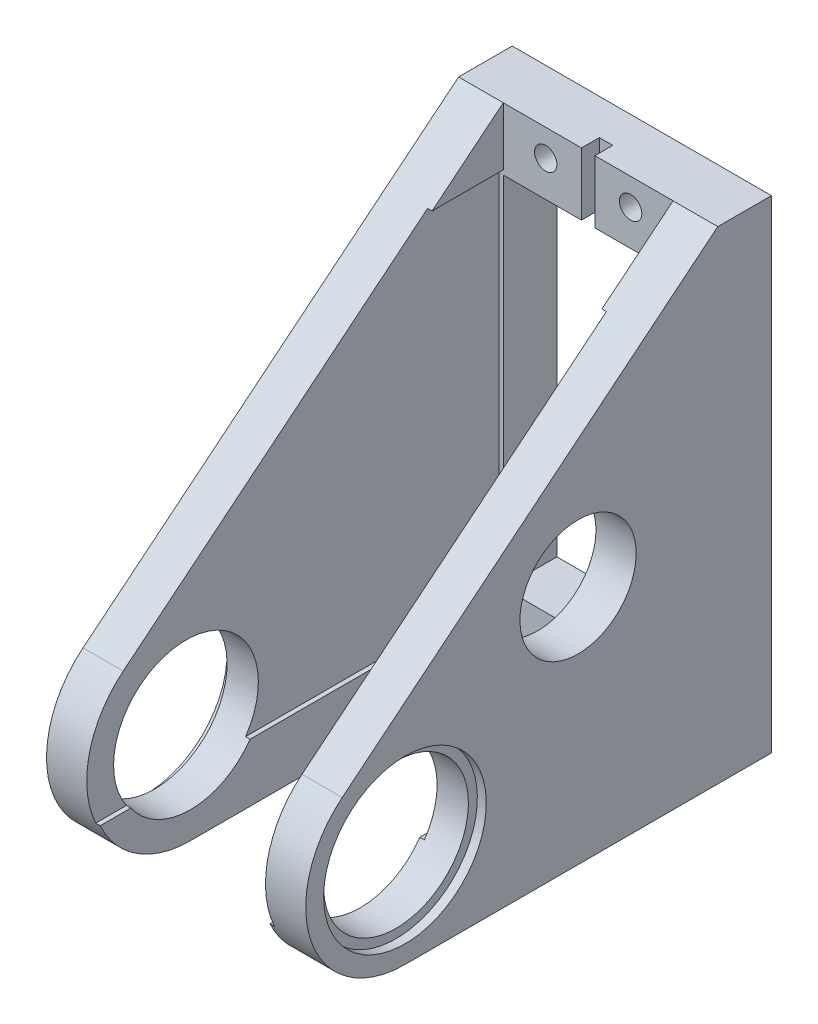
SolidWorks part; units mm, degrees
ref_plane "Спереди" through (0, 0, 0) normal (0, 0, 1) x (1, 0, 0)
ref_plane "Сверху" through (0, 0, 0) normal (0, 1, 0) x (1, 0, 0)
ref_plane "Справа" through (0, 0, 0) normal (1, 0, 0) x (0, 0, -1)
sketch "Эскиз1" plane through (0, 0, 0) normal (0, 0, 1) x (1, 0, 0)
  line L0 (4.75, 4) -> (14.25, 4) construction
  line L1 (0, 0) -> (19, 0)
  line L2 (0, 0) -> (0, -40)
  line L3 (0, -40) -> (19, -40)
  line L4 (19, 0) -> (19, -40)
  line L5 (-5, 7) -> (24, 7)
  line L6 (-5, 7) -> (-5, -47)
  line L7 (-5, -47) -> (24, -47)
  line L8 (24, 7) -> (24, -47)
  line L9 (9.5, 4) -> (9.5, 0) construction
  line L10 (9.5, -40) -> (9.5, -44) construction
  line L11 (4.75, -44) -> (14.25, -44) construction
  circle A0 centre (4.75, 4) radius 1.25
  circle A1 centre (14.25, 4) radius 1.25
  circle A2 centre (4.75, -44) radius 1.25
  circle A3 centre (14.25, -44) radius 1.25
  point P19 (9.5, -44)
  dimension "D8" = 2.5
  dimension "D1" = 40
  dimension "D2" = 19
  dimension "D3" = 7
  dimension "D4" = 7
  dimension "D5" = 5
  dimension "D6" = 5
  dimension "D7" = 9.5
  dimension "D9" = 4
extrude "Бобышка-Вытянуть1" add sketch "Эскиз1" along normal blind 6
sketch "Эскиз2" plane through (0, 0, 6) normal (0, 0, 1) x (1, 0, 0)
  line L0 (9.5, 0) -> (9.5, -40) construction
  line L1 (19, 0) -> (0, 0) construction
  line L2 (0, -40) -> (19, -40) construction
  line L3 (24, 7) -> (-5, 7) construction
  line L4 (8.75, -40) -> (10.25, -40)
  line L5 (8.75, -40) -> (8.75, -47)
  line L6 (8.75, -47) -> (10.25, -47)
  line L7 (10.25, -40) -> (10.25, -47)
  line L8 (10.25, 0) -> (8.75, 0)
  line L9 (10.25, 0) -> (10.25, 7)
  line L10 (10.25, 7) -> (8.75, 7)
  line L11 (8.75, 0) -> (8.75, 7)
  line L12 (-5, -47) -> (24, -47) construction
  point P14 (9.5, 0)
  point P15 (9.5, -40)
  dimension "D1" = 1.5
extrude "Вырез-Вытянуть1" cut sketch "Эскиз2" against normal blind 2
sketch "Эскиз3" plane through (24, 0, 0) normal (1, 0, 0) x (0, 0, -1)
  line L0 (-6, -47) -> (-41, -47)
  line L1 (-48.0193, -27.3012) -> (-6, 7)
  line L2 (-6, -47) -> (-6, 7) construction
  line L3 (-6, 7) -> (-6, -47)
  arc A0 (-48.0193, -27.3012) -> (-41, -47) centre (-41, -35.9) ccw
  circle A1 centre (-41, -35.9) radius 8.1
  dimension "D1" = 3
  dimension "D3" = 16.2
  dimension "D2" = 35
extrude "Бобышка-Вытянуть2" add sketch "Эскиз3" against normal blind 5
sketch "Эскиз4" plane through (24, 0, 0) normal (1, 0, 0) x (0, 0, -1)
  circle A0 centre (-41, -35.9) radius 9.1
  dimension "D1" = 18.2
extrude "Вырез-Вытянуть2" cut sketch "Эскиз4" against normal blind 1
ref_plane "Плоскость1" through (9.5, 0, 0) normal (-1, 0, 0) x (0, 0, 1)
mirror "Зеркальное отражение1" about plane through (9.5, 0, 0) normal (-1, 0, 0) of "Вырез-Вытянуть2", "Бобышка-Вытянуть2"
sketch "Эскиз5" plane through (0, 0, 6) normal (0, 0, 1) x (1, 0, 0)
  line L0 (-0.5, 0.5) -> (19.5, 0.5)
  line L1 (0, 0) -> (19, 0) construction
  line L2 (0, 0) -> (0, -40) construction
  line L3 (0, -40) -> (19, -40) construction
  line L4 (19, 0) -> (19, -40) construction
  line L5 (19.5, 0.5) -> (19.5, -40.5)
  line L6 (-0.5, -40.5) -> (19.5, -40.5)
  line L7 (-0.5, 0.5) -> (-0.5, -40.5)
  dimension "D1" = 0.5
extrude "Вырез-Вытянуть3" cut sketch "Эскиз5" along normal through all
sketch "Эскиз6" plane through (24, 0, 0) normal (1, 0, 0) x (0, 0, -1)
  line L0 (-41, -35.9) -> (-21.6334, -20.0907) construction
  line L1 (-6, 7) -> (-48.0193, -27.3012) construction
  line L2 (-41, -35.9) -> (-21.6334, -35.9) construction
  line L3 (-21.6334, -35.9) -> (-21.6334, -20.0907) construction
  circle A0 centre (-21.6334, -20.0907) radius 6.5
  dimension "D1" = 13
  dimension "D2" = 25
  dimension "D3" = 19.3666
  dimension "D4" = 15.8093
extrude "Вырез-Вытянуть4" cut sketch "Эскиз6" against normal blind 5
sketch "Эскиз7" plane through (24, 0, 0) normal (1, 0, 0) x (0, 0, -1)
  line L0 (-6, 7) -> (-6, -47) construction
  line L1 (-34.5, -40.7332) -> (-34.5, -31.0668) construction
  circle A0 centre (-41, -35.9) radius 8.1 construction
  circle A1 centre (-41, -35.9) radius 8.1 construction
  dimension "D1" = 28.5
  dimension "D2" = 9.6664
